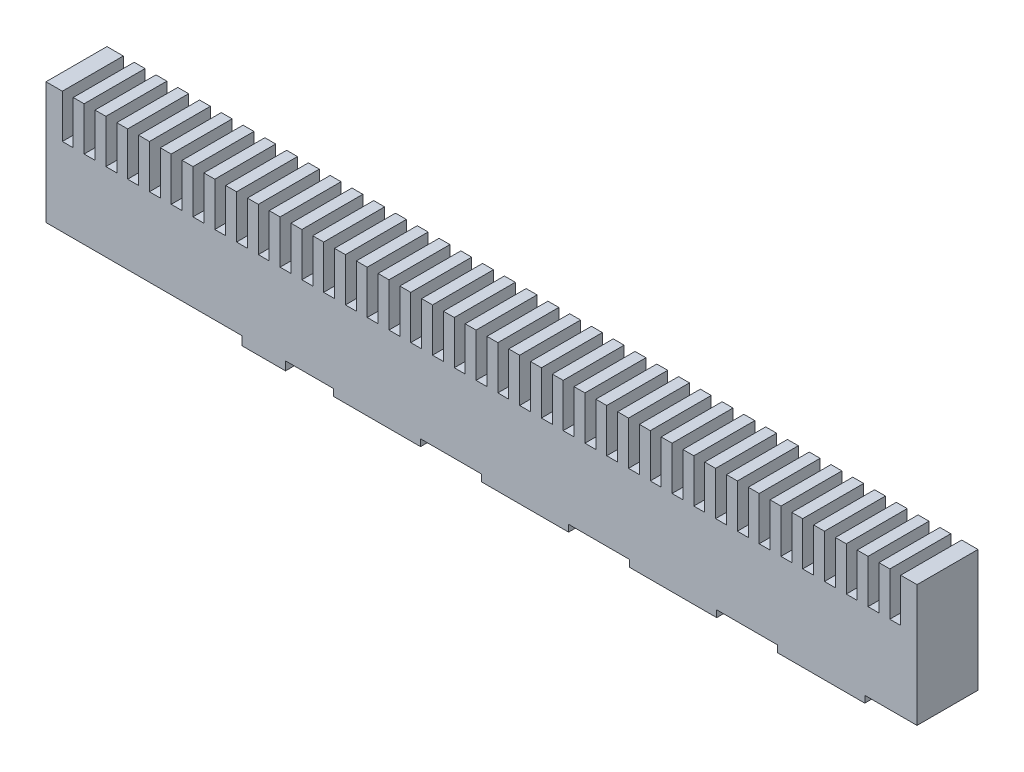
SolidWorks part; units mm, degrees
material "Brass"
ref_plane "Front Plane" through (0, 0, 0) normal (0, 0, 1) x (1, 0, 0)
ref_plane "Top Plane" through (0, 0, 0) normal (0, 1, 0) x (1, 0, 0)
ref_plane "Right Plane" through (0, 0, 0) normal (1, 0, 0) x (0, 0, -1)
sketch "Sketch1" plane through (0, 0, 0) normal (0, 1, 0) x (1, 0, 0)
  line L1 (0, 0) -> (200, 0)
  line L2 (0, 0) -> (0, 14)
  line L3 (0, 14) -> (200, 14)
  line L4 (200, 0) -> (200, 14)
  dimension "D1" = 200
  dimension "D2" = 14
extrude "Boss-Extrude1" add sketch "Sketch1" along normal blind 30
sketch "Sketch2" plane through (0, 0, 0) normal (0, -1, 0) x (1, 0, 0)
  line L0 (200, -14) -> (0, -14) construction
  line L1 (200, 0) -> (188, 0)
  line L2 (200, 0) -> (200, -14)
  line L3 (200, -14) -> (188, -14)
  line L4 (188, 0) -> (188, -14)
  line L5 (0, 0) -> (200, 0) construction
  line L6 (168, -14) -> (154, -14)
  line L7 (168, -14) -> (168, 0)
  line L8 (168, 0) -> (154, 0)
  line L9 (154, -14) -> (154, 0)
  line L11 (134, -14) -> (120, -14)
  line L12 (134, -14) -> (134, 0)
  line L13 (134, 0) -> (120, 0)
  line L14 (120, -14) -> (120, 0)
  line L15 (100, -14) -> (86, -14)
  line L16 (100, -14) -> (100, 0)
  line L17 (100, 0) -> (86, 0)
  line L18 (86, -14) -> (86, 0)
  line L19 (66, -14) -> (55, -14)
  line L20 (66, -14) -> (66, 0)
  line L21 (66, 0) -> (55, 0)
  line L22 (55, -14) -> (55, 0)
  line L23 (0, -14) -> (45, -14)
  line L24 (0, -14) -> (0, 0)
  line L25 (0, 0) -> (45, 0)
  line L26 (45, -14) -> (45, 0)
  dimension "D1" = 12
  dimension "D2" = 32
  dimension "D3" = 46
  dimension "D4" = 66
  dimension "D5" = 80
  dimension "D6" = 100
  dimension "D7" = 114
  dimension "D8" = 134
  dimension "D9" = 145
  dimension "D10" = 155
extrude "Cut-Extrude1" cut sketch "Sketch2" against normal blind 2
sketch "Sketch3" plane through (0, 0, 0) normal (0, -1, 0) x (1, 0, 0)
  line L1 (66, -14) -> (86, -14)
  line L2 (66, -14) -> (66, 0)
  line L3 (66, 0) -> (86, 0)
  line L4 (86, -14) -> (86, 0)
  line L5 (100, -14) -> (120, -14)
  line L6 (100, -14) -> (100, 0)
  line L7 (100, 0) -> (120, 0)
  line L8 (120, -14) -> (120, 0)
  line L9 (134, -14) -> (154, -14)
  line L10 (134, -14) -> (134, 0)
  line L11 (134, 0) -> (154, 0)
  line L12 (154, -14) -> (154, 0)
  line L13 (168, -14) -> (188, -14)
  line L14 (168, -14) -> (168, 0)
  line L15 (168, 0) -> (188, 0)
  line L16 (188, -14) -> (188, 0)
extrude "Cut-Extrude2" cut sketch "Sketch3" against normal blind 0.435
sketch "Sketch5" plane through (0, 0, 0) normal (0, 0, 1) x (1, 0, 0)
  line L0 (3.75, 30) -> (3.75, 20)
  line L1 (0, 30) -> (200, 30) construction
  line L2 (3.75, 20) -> (6.25, 20)
  line L3 (6.25, 20) -> (6.25, 30)
  line L4 (6.25, 30) -> (8.75, 30)
  line L5 (0, 30) -> (0, 2) construction
  line L6 (8.75, 30) -> (8.75, 20)
  line L7 (8.75, 20) -> (11.25, 20)
  line L8 (11.25, 20) -> (11.25, 30)
  line L9 (11.25, 30) -> (13.75, 30)
  line L10 (13.75, 30) -> (13.75, 20)
  line L11 (13.75, 20) -> (16.25, 20)
  line L12 (16.25, 20) -> (16.25, 30)
  line L13 (16.25, 30) -> (18.75, 30)
  line L14 (18.75, 30) -> (18.75, 20)
  line L15 (18.75, 20) -> (21.25, 20)
  line L16 (21.25, 20) -> (21.25, 30)
  line L17 (21.25, 30) -> (23.75, 30)
  line L18 (23.75, 30) -> (23.75, 20)
  line L19 (23.75, 20) -> (26.25, 20)
  line L20 (26.25, 20) -> (26.25, 30)
  line L21 (26.25, 30) -> (28.75, 30)
  line L22 (28.75, 30) -> (28.75, 20)
  line L23 (28.75, 20) -> (31.25, 20)
  line L24 (31.25, 20) -> (31.25, 30)
  line L25 (31.25, 30) -> (33.75, 30)
  line L26 (33.75, 30) -> (33.75, 20)
  line L27 (33.75, 20) -> (36.25, 20)
  line L28 (36.25, 20) -> (36.25, 30)
  line L29 (36.25, 30) -> (38.75, 30)
  line L30 (38.75, 30) -> (38.75, 20)
  line L31 (38.75, 20) -> (41.25, 20)
  line L32 (41.25, 20) -> (41.25, 30)
  line L33 (41.25, 30) -> (43.75, 30)
  line L34 (43.75, 30) -> (43.75, 20)
  line L35 (43.75, 20) -> (46.25, 20)
  line L36 (46.25, 20) -> (46.25, 30)
  line L37 (46.25, 30) -> (48.75, 30)
  line L38 (48.75, 30) -> (48.75, 20)
  line L39 (48.75, 20) -> (51.25, 20)
  line L40 (51.25, 20) -> (51.25, 30)
  line L41 (51.25, 30) -> (53.75, 30)
  line L42 (53.75, 30) -> (53.75, 20)
  line L43 (53.75, 20) -> (56.25, 20)
  line L44 (56.25, 20) -> (56.25, 30)
  line L45 (56.25, 30) -> (58.75, 30)
  line L46 (58.75, 30) -> (58.75, 20)
  line L47 (58.75, 20) -> (61.25, 20)
  line L48 (61.25, 20) -> (61.25, 30)
  line L49 (61.25, 30) -> (63.75, 30)
  line L50 (63.75, 30) -> (63.75, 20)
  line L51 (63.75, 20) -> (66.25, 20)
  line L52 (66.25, 20) -> (66.25, 30)
  line L53 (66.25, 30) -> (68.75, 30)
  line L54 (68.75, 30) -> (68.75, 20)
  line L55 (68.75, 20) -> (71.25, 20)
  line L56 (71.25, 20) -> (71.25, 30)
  line L57 (71.25, 30) -> (73.75, 30)
  line L58 (73.75, 30) -> (73.75, 20)
  line L59 (73.75, 20) -> (76.25, 20)
  line L60 (76.25, 20) -> (76.25, 30)
  line L61 (76.25, 30) -> (78.75, 30)
  line L62 (78.75, 30) -> (78.75, 20)
  line L63 (78.75, 20) -> (81.25, 20)
  line L64 (81.25, 20) -> (81.25, 30)
  line L65 (81.25, 30) -> (83.75, 30)
  line L66 (83.75, 30) -> (83.75, 20)
  line L67 (83.75, 20) -> (86.25, 20)
  line L68 (86.25, 20) -> (86.25, 30)
  line L69 (86.25, 30) -> (88.75, 30)
  line L70 (88.75, 30) -> (88.75, 20)
  line L71 (88.75, 20) -> (91.25, 20)
  line L72 (91.25, 20) -> (91.25, 30)
  line L73 (91.25, 30) -> (93.75, 30)
  line L74 (93.75, 30) -> (93.75, 20)
  line L75 (93.75, 20) -> (96.25, 20)
  line L76 (96.25, 20) -> (96.25, 30)
  line L77 (96.25, 30) -> (98.75, 30)
  line L78 (98.75, 30) -> (98.75, 20)
  line L79 (98.75, 20) -> (101.25, 20)
  line L80 (101.25, 20) -> (101.25, 30)
  line L81 (101.25, 30) -> (103.75, 30)
  line L82 (103.75, 30) -> (103.75, 20)
  line L83 (103.75, 20) -> (106.25, 20)
  line L84 (106.25, 20) -> (106.25, 30)
  line L85 (106.25, 30) -> (108.75, 30)
  line L86 (108.75, 30) -> (108.75, 20)
  line L87 (108.75, 20) -> (111.25, 20)
  line L88 (111.25, 20) -> (111.25, 30)
  line L89 (111.25, 30) -> (113.75, 30)
  line L90 (113.75, 30) -> (113.75, 20)
  line L91 (113.75, 20) -> (116.25, 20)
  line L92 (116.25, 20) -> (116.25, 30)
  line L93 (116.25, 30) -> (118.75, 30)
  line L94 (118.75, 30) -> (118.75, 20)
  line L95 (118.75, 20) -> (121.25, 20)
  line L96 (121.25, 20) -> (121.25, 30)
  line L97 (121.25, 30) -> (123.75, 30)
  line L98 (123.75, 30) -> (123.75, 20)
  line L99 (123.75, 20) -> (126.25, 20)
  line L100 (126.25, 20) -> (126.25, 30)
  line L101 (126.25, 30) -> (128.75, 30)
  line L102 (128.75, 30) -> (128.75, 20)
  line L103 (128.75, 20) -> (131.25, 20)
  line L104 (131.25, 20) -> (131.25, 30)
  line L105 (131.25, 30) -> (133.75, 30)
  line L106 (133.75, 30) -> (133.75, 20)
  line L107 (133.75, 20) -> (136.25, 20)
  line L108 (136.25, 20) -> (136.25, 30)
  line L109 (136.25, 30) -> (138.75, 30)
  line L110 (138.75, 30) -> (138.75, 20)
  line L111 (138.75, 20) -> (141.25, 20)
  line L112 (141.25, 20) -> (141.25, 30)
  line L113 (141.25, 30) -> (143.75, 30)
  line L114 (143.75, 30) -> (143.75, 20)
  line L115 (143.75, 20) -> (146.25, 20)
  line L116 (146.25, 20) -> (146.25, 30)
  line L117 (146.25, 30) -> (148.75, 30)
  line L118 (148.75, 30) -> (148.75, 20)
  line L119 (148.75, 20) -> (151.25, 20)
  line L120 (151.25, 20) -> (151.25, 30)
  line L121 (151.25, 30) -> (153.75, 30)
  line L122 (153.75, 30) -> (153.75, 20)
  line L123 (153.75, 20) -> (156.25, 20)
  line L124 (156.25, 20) -> (156.25, 30)
  line L125 (156.25, 30) -> (158.75, 30)
  line L126 (158.75, 30) -> (158.75, 20)
  line L127 (158.75, 20) -> (161.25, 20)
  line L128 (161.25, 20) -> (161.25, 30)
  line L129 (161.25, 30) -> (163.75, 30)
  line L130 (163.75, 30) -> (163.75, 20)
  line L131 (163.75, 20) -> (166.25, 20)
  line L132 (166.25, 20) -> (166.25, 30)
  line L133 (166.25, 30) -> (168.75, 30)
  line L134 (168.75, 30) -> (168.75, 20)
  line L135 (168.75, 20) -> (171.25, 20)
  line L136 (171.25, 20) -> (171.25, 30)
  line L137 (171.25, 30) -> (173.75, 30)
  line L138 (173.75, 30) -> (173.75, 20)
  line L139 (173.75, 20) -> (176.25, 20)
  line L140 (176.25, 20) -> (176.25, 30)
  line L141 (176.25, 30) -> (178.75, 30)
  line L142 (178.75, 30) -> (178.75, 20)
  line L143 (178.75, 20) -> (181.25, 20)
  line L144 (181.25, 20) -> (181.25, 30)
  line L145 (181.25, 30) -> (183.75, 30)
  line L146 (183.75, 30) -> (183.75, 20)
  line L147 (183.75, 20) -> (186.25, 20)
  line L148 (186.25, 20) -> (186.25, 30)
  line L149 (186.25, 30) -> (188.75, 30)
  line L150 (188.75, 30) -> (188.75, 20)
  line L151 (188.75, 20) -> (191.25, 20)
  line L152 (191.25, 20) -> (191.25, 30)
  line L153 (191.25, 30) -> (193.75, 30)
  line L154 (193.75, 30) -> (193.75, 20)
  line L155 (193.75, 20) -> (196.25, 20)
  line L156 (196.25, 20) -> (196.25, 30)
  line L157 (3.75, 30) -> (3.75, 37.4519)
  line L158 (196.25, 30) -> (198.75, 30) [skipped]
  line L159 (3.75, 37.4519) -> (196.25, 37.4519)
  line L160 (196.25, 37.4519) -> (196.25, 30)
  dimension "D1" = 2.5
  dimension "D2" = 3.75
  dimension "D3" = 10
  dimension "D4" = 39
extrude "Cut-Extrude4" cut sketch "Sketch5" against normal through all
